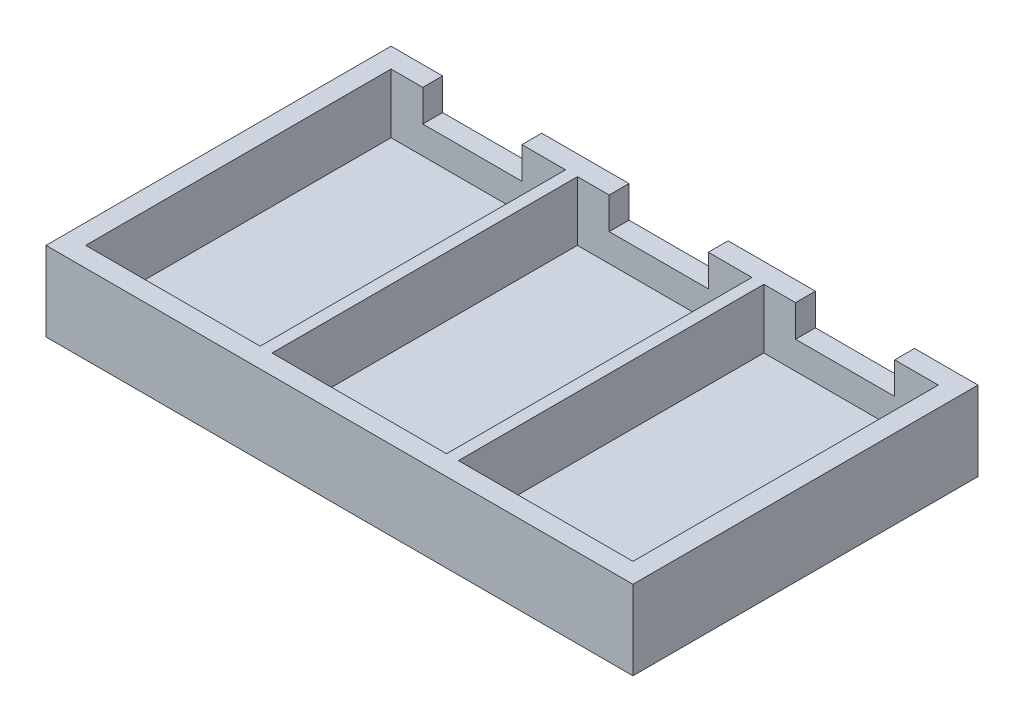
SolidWorks part; units mm, degrees
ref_plane "Frontal Plane" through (0, 0, 0) normal (0, 0, 1) x (1, 0, 0)
ref_plane "Horizontal Plane" through (0, 0, 0) normal (0, 1, 0) x (1, 0, 0)
ref_plane "Profile Plane" through (0, 0, 0) normal (1, 0, 0) x (0, 0, -1)
sketch "Sketch1" plane through (0, 0, 0) normal (0, 1, 0) x (1, 0, 0)
  line L0 (0, 43.5) -> (0, -43.5)
  line L1 (0, -43.5) -> (148, -43.5)
  line L2 (148, -43.5) -> (148, 43.5)
  line L3 (148, 43.5) -> (0, 43.5)
  point P4 (0, 0)
  dimension "D1" = 148
  dimension "D2" = 87
extrude "Boss-Extrude1" add sketch "Sketch1" along normal blind 20
shell "Shell1" thickness 5
sketch "Sketch2" plane through (0, 20, 0) normal (0, 1, 0) x (1, 0, 0)
  line L0 (49, 38.5) -> (49, -38.5)
  line L1 (143, 38.5) -> (5, 38.5) construction
  line L2 (5, -38.5) -> (143, -38.5) construction
  line L3 (49, -38.5) -> (52, -38.5)
  line L4 (5, -38.5) -> (143, -38.5) construction
  line L5 (52, -38.5) -> (52, 38.5)
  line L6 (52, 38.5) -> (49, 38.5)
  line L7 (5, 38.5) -> (5, -38.5) construction
  line L8 (99, 38.5) -> (96, 38.5)
  line L9 (96, 38.5) -> (96, -38.5)
  line L10 (96, -38.5) -> (99, -38.5)
  line L11 (99, -38.5) -> (99, 38.5)
  dimension "D1" = 3
  dimension "D2" = 44
  dimension "D4" = 44
  dimension "D3" = 2
extrude "Boss-Extrude2" add sketch "Sketch2" against normal up to next
sketch "Sketch3" plane through (0, 20, 0) normal (0, 1, 0) x (1, 0, 0)
  line L0 (13, 43.5) -> (13, 38.5)
  line L1 (148, 43.5) -> (0, 43.5) construction
  line L2 (49, 38.5) -> (5, 38.5) construction
  line L3 (13, 38.5) -> (38, 38.5)
  line L4 (38, 38.5) -> (38, 43.5)
  line L5 (38, 43.5) -> (13, 43.5)
  line L6 (49, 38.5) -> (5, 38.5) construction
  line L7 (85, 43.5) -> (60, 43.5)
  line L8 (60, 43.5) -> (60, 38.5)
  line L9 (60, 38.5) -> (85, 38.5)
  line L10 (85, 38.5) -> (85, 43.5)
  line L11 (132, 43.5) -> (107, 43.5)
  line L12 (107, 43.5) -> (107, 38.5)
  line L13 (107, 38.5) -> (132, 38.5)
  line L14 (132, 38.5) -> (132, 43.5)
  line L15 (38, 43.5) -> (85, 43.5) construction
  point P10 (27, 38.5)
  point P11 (25.5, 43.5)
  dimension "D1" = 25
  dimension "D2" = 1.5
  dimension "D4" = 47
  dimension "D3" = 3
extrude "Cut-Extrude1" cut sketch "Sketch3" against normal offset from surface (8 mm away) 7 up to face at (27, 5, 0)
